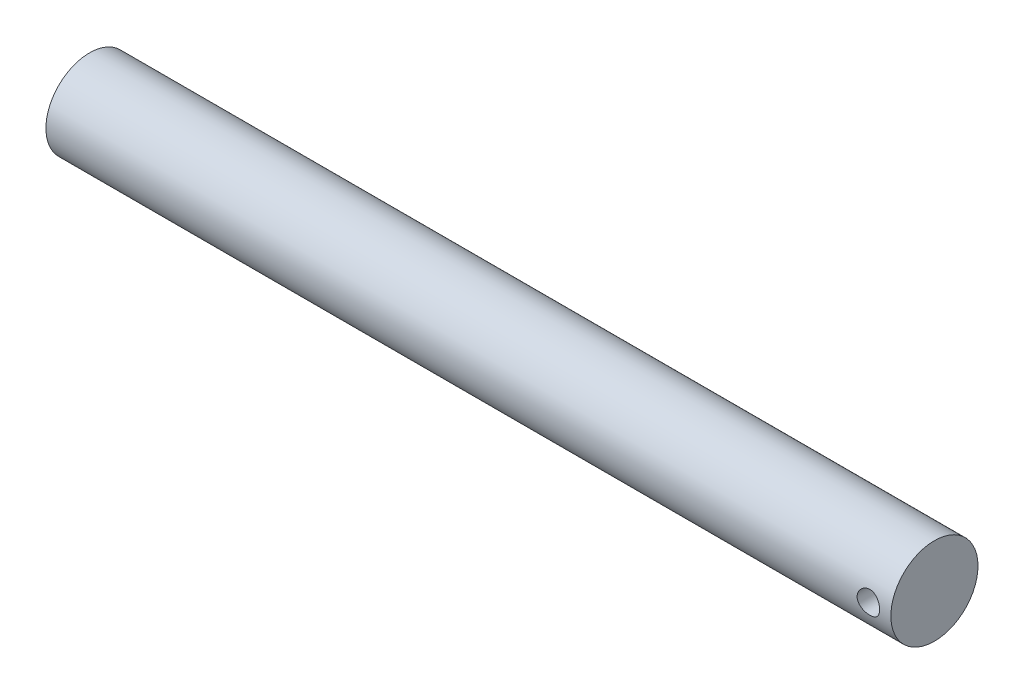
SolidWorks part; units mm, degrees
ref_plane "Front Plane" through (0, 0, 0) normal (0, 0, 1) x (1, 0, 0)
ref_plane "Top Plane" through (0, 0, 0) normal (0, 1, 0) x (1, 0, 0)
ref_plane "Right Plane" through (0, 0, 0) normal (1, 0, 0) x (0, 0, -1)
sketch "Sketch1" plane through (0, 0, 0) normal (1, 0, 0) x (0, 0, -1)
  circle A0 centre (0, 0) radius 4.85
  dimension "D1" = 9.7
extrude "Boss-Extrude1" add sketch "Sketch1" along normal blind 103.5536
sketch "Sketch2" plane through (0, 0, 0) normal (0, 0, 1) x (1, 0, 0)
  line L0 (103.5536, -4.85) -> (103.5536, 4.85) construction
  circle A0 centre (101.0536, 0) radius 1.25
  dimension "D1" = 2.5
  dimension "D2" = 2.5
extrude "Cut-Extrude1" cut sketch "Sketch2" against normal through all both and the other way through all
sketch "Sketch3" plane through (0, 0, 0) normal (0, 1, 0) x (1, 0, 0)
  line L1 (-32.5096, 52.2507) -> (9.5194, 52.2507)
  line L2 (-32.5096, 52.2507) -> (-32.5096, -19.2442)
  line L3 (-32.5096, -19.2442) -> (9.5194, -19.2442)
  line L4 (9.5194, 52.2507) -> (9.5194, -19.2442)
  line L5 (-32.5096, 52.2507) -> (9.5194, -19.2442) construction
  line L6 (-32.5096, -19.2442) -> (9.5194, 52.2507) construction
  point P0 (-11.4951, 16.5032)
extrude "Cut-Extrude2" cut sketch "Sketch3" against normal through all both and the other way through all
scale "Scale1" scale about centroid uniform scaling yes scale factor 1.5
